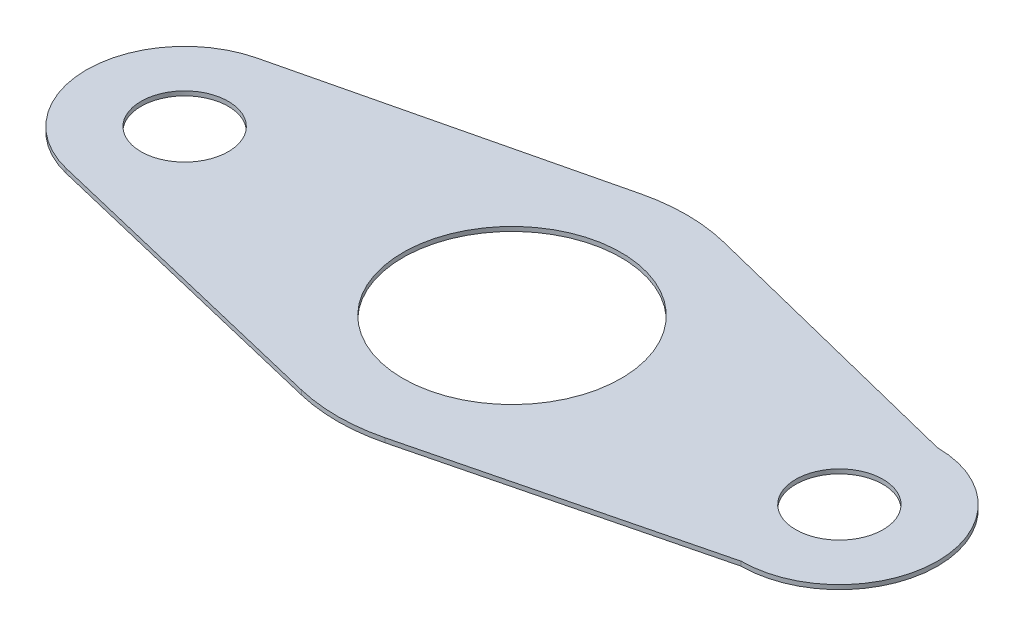
SolidWorks part; units mm, degrees
ref_plane "Front Plane" through (0, 0, 0) normal (0, 0, 1) x (1, 0, 0)
ref_plane "Top Plane" through (0, 0, 0) normal (0, 1, 0) x (1, 0, 0)
ref_plane "Right Plane" through (0, 0, 0) normal (1, 0, 0) x (0, 0, -1)
sketch "Sketch1" plane through (0, 0, 0) normal (0, 1, 0) x (1, 0, 0)
  line L0 (0, 0) -> (0, 40) construction
  line L1 (-75, 0) -> (75, 0) construction
  line L2 (0.1895, 41.1809) -> (0, 41.1355)
  line L3 (-80.25, -21.8789) -> (-9.3333, -38.8959)
  line L4 (75, 22.5) -> (9.6908, 38.8083)
  line L5 (75, -22.5) -> (9.6908, -38.8083)
  line L6 (0.1895, 41.1809) -> (0, 41.2282)
  line L7 (0, 41.1355) -> (0, 41.2282) construction
  line L8 (-9.3333, 38.8959) -> (-80.25, 21.8789)
  line L9 (75, 22.5) -> (75, -32.1867) construction
  circle A0 centre (-75, 0) radius 22.5
  circle A1 centre (75, 0) radius 22.5
  circle A2 centre (0, 0) radius 40
  circle A3 centre (-75, 0) radius 10
  circle A4 centre (0, 0) radius 25
  circle A5 centre (75, 0) radius 10
  dimension "D1" = 80
  dimension "D2" = 22.5
  dimension "D3" = 75
  dimension "D5" = 22.5
  dimension "D6" = 20
  dimension "D7" = 20
  dimension "D8" = 50
  dimension "D4" = 75
extrude "Boss-Extrude1" add sketch "Sketch1" along normal blind 1 contours A0 A3 | A2 L8 A0 L3 | A2 A4 | A2 L5 A1 L4 | A1 A5
sketch "Sketch2" plane through (0, 1, 0) normal (0, 1, 0) x (1, 0, 0)
  line L0 (75, -22.5) -> (75, 22.5) construction
